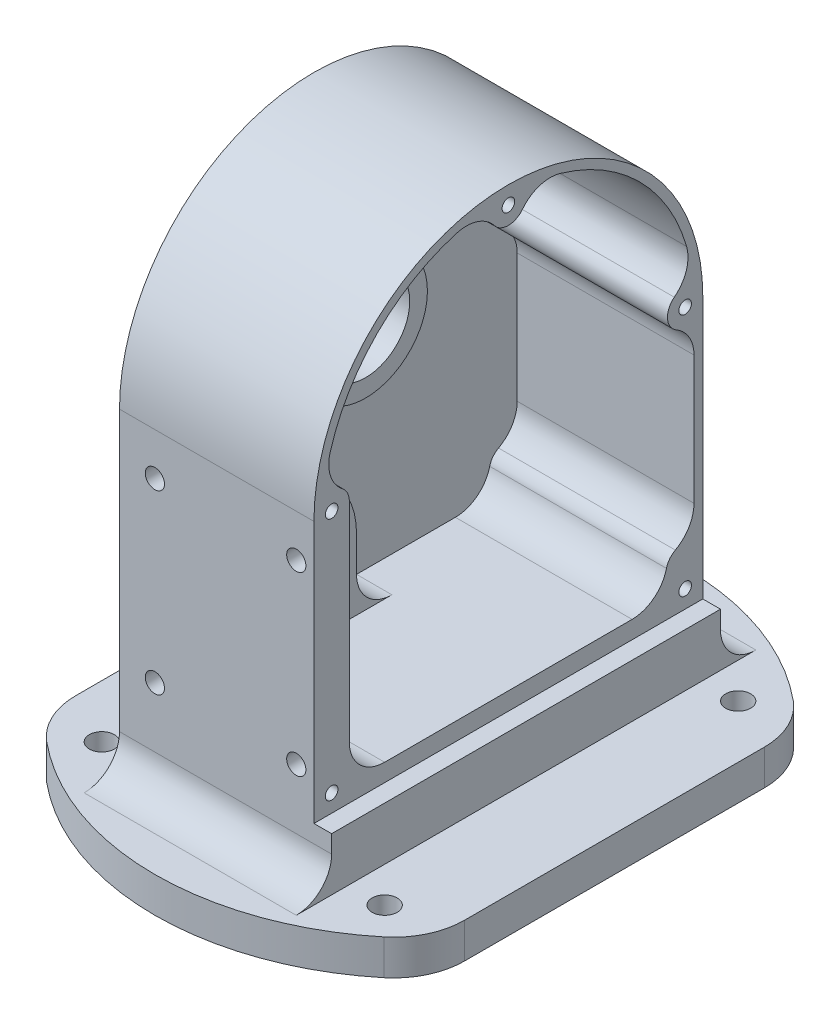
SolidWorks part; units mm, degrees
material "6061 Alloy"
ref_plane "Front Plane" through (0, 0, 0) normal (0, 0, 1) x (1, 0, 0)
ref_plane "Top Plane" through (0, 0, 0) normal (0, 1, 0) x (1, 0, 0)
ref_plane "Right Plane" through (0, 0, 0) normal (1, 0, 0) x (0, 0, -1)
sketch "Sketch1" plane through (0, 0, 0) normal (1, 0, 0) x (0, 0, -1)
  line L2 (-34.925, 5.715) -> (-34.925, -41.275)
  line L3 (-34.925, -41.275) -> (34.925, -41.275)
  line L4 (34.925, 5.715) -> (34.925, -41.275)
  arc A0 (34.925, 5.715) -> (-34.925, 5.715) centre (0, 5.715) ccw
  point P0 (0, 0)
  dimension "D1" = 41.275
  dimension "D3" = 46.99
  dimension "D4" = 69.85
extrude "Boss-Extrude1" add sketch "Sketch1" along normal mid plane 34.925
sketch "Sketch2" plane through (-17.4625, 0, 0) normal (-1, 0, 0) x (0, 0, 1)
  line L2 (34.925, 5.715) -> (34.925, -41.275) construction
  circle A0 centre (15.875, -25.3935) radius 11.254
  point P2 (0, 5.715)
  dimension "D1" = 22.508
  dimension "D2" = 34.925
  dimension "D3" = 19.05
extrude "Cut-Extrude1" cut sketch "Sketch2" against normal blind 6.35
sketch "Sketch3" plane through (-11.1125, 0, 0) normal (-1, 0, 0) x (0, 0, 1)
  circle A0 centre (15.875, -25.3935) radius 5.127
  dimension "D1" = 10.254
extrude "Cut-Extrude2" cut sketch "Sketch3" against normal through all
sketch "Sketch4" plane through (17.4625, 0, 0) normal (1, 0, 0) x (0, 0, -1)
  circle A0 centre (-15.875, -25.3935) radius 11.254
  circle A1 centre (-15.875, -25.3935) radius 11.254 construction
extrude "Cut-Extrude3" cut sketch "Sketch4" against normal offset from surface (25.4 mm away) 3.175 up to face at (-11.1125, -25.3935, 21.002)
hole_wizard "CSK for M2.5 Flat Head Machine Screw1" positions "Sketch6" profile "Sketch5" countersink size "M2.5" standard "Ansi Metric" end condition through all
sketch "Sketch6" plane through (-7.9375, 0, 0) normal (1, 0, 0) x (0, 0, -1)
  line L0 (-15.875, -18.3935) -> (-15.875, -25.3935) construction
  circle A0 centre (-15.875, -25.3935) radius 5.127 construction
  point P0 (-15.875, -18.3935)
  dimension "D1" = 7
sketch "Sketch5" plane through (-7.9375, -18.3935, 15.875) normal (0, 1, 0) x (0, 0, -1)
  line L0 (0, 0) -> (0, 9.525)
  line L1 (0, 9.525) -> (1.45, 9.525)
  line L2 (1.45, 9.525) -> (1.45, 1.3)
  line L3 (1.45, 1.3) -> (2.75, 0)
  line L5 (2.75, 0) -> (0, 0)
  line L6 (-1.45, 1.3) -> (-2.75, 0) construction
  line L11 (0, -6.35) -> (0, 107.95) construction
  dimension "Thru Hole Dia." = 2.9
  dimension "Thru Hole Depth" = 9.525
  dimension "Near C'Sink Dia." = 5.5
  dimension "Near C'Sink Angle" = 90
pattern_circular "CirPattern1" count 3 over 360 about axis through (0, -25.3935, 15.875) along (1, 0, 0) of "CSK for M2.5 Flat Head Machine Screw1"
sketch "Sketch7" plane through (17.4625, 0, 0) normal (1, 0, 0) x (0, 0, -1)
  line L0 (28.575, -38.1) -> (-28.575, -38.1)
  line L1 (-28.575, -38.1) -> (-28.575, 5.715)
  line L3 (28.575, 5.715) -> (28.575, -38.1)
  line L5 (34.925, -41.275) -> (34.925, 5.715) construction
  line L6 (-34.925, 5.715) -> (-34.925, -41.275) construction
  line L7 (-34.925, -41.275) -> (34.925, -41.275) construction
  arc A0 (28.575, 5.715) -> (-28.575, 5.715) centre (0, 5.715) ccw
  dimension "D2" = 6.35
  dimension "D3" = 6.35
  dimension "D4" = 3.175
extrude "Cut-Extrude4" cut sketch "Sketch7" against normal up to surface (25.4 mm away) up to face at (-7.9375, -25.3935, 27.129)
sketch "Sketch8" plane through (-7.9375, 0, 0) normal (1, 0, 0) x (0, 0, -1)
  line L0 (-28.575, 5.715) -> (-28.575, -38.1) construction
  line L2 (-15.875, -11.3935) -> (-28.575, -11.3935)
  line L3 (-28.575, -38.1) -> (28.575, -38.1) construction
  line L4 (-1.875, -38.1) -> (-1.875, -25.3935)
  line L6 (-28.575, -11.3935) -> (-28.575, 5.715)
  line L8 (28.575, 5.715) -> (28.575, -38.1)
  line L9 (28.575, -38.1) -> (-1.875, -38.1)
  arc A0 (-1.875, -25.3935) -> (-15.875, -11.3935) centre (-15.875, -25.3935) ccw
  arc A1 (28.575, 5.715) -> (-28.575, 5.715) centre (0, 5.715) ccw construction
  arc A2 (28.575, 5.715) -> (-28.575, 5.715) centre (0, 5.715) ccw construction
  arc A3 (28.575, 5.715) -> (-28.575, 5.715) centre (0, 5.715) ccw
  dimension "D1" = 14
extrude "Cut-Extrude5" cut sketch "Sketch8" against normal offset from surface (6.35 mm away) 3.175 up to face at (-17.4625, -25.3935, 27.129)
fillet "Fillet1" radius 6.35 4 edges at (4.7625, -38.1, 28.575) (1.5875, -38.1, -28.575) (-11.1125, -38.1, 1.875) (-11.1125, -11.3935, 28.575)
sketch "Sketch9" plane through (-14.2875, 0, 0) normal (1, 0, 0) x (0, 0, -1)
  circle A0 centre (0, 5.715) radius 7.9375
  arc A1 (34.925, 5.715) -> (-34.925, 5.715) centre (0, 5.715) ccw construction
  dimension "D2" = 15.875
extrude "Cut-Extrude6" cut sketch "Sketch9" against normal through all
chamfer "Chamfer1" distance 1.27 angle 45 1 edges at (-17.4625, -25.3935, 27.129)
sketch "Sketch10" plane through (-14.2875, 0, 0) normal (1, 0, 0) x (0, 0, -1)
  circle A0 centre (0, 5.715) radius 11.1125
  circle A1 centre (0, 5.715) radius 7.9375 construction
  circle A2 centre (0, 5.715) radius 7.9375
  dimension "D1" = 3.175
extrude "Boss-Extrude2" add sketch "Sketch10" along normal offset from surface (6.096 mm away) 9.271 up to face at (-17.4625, -25.3935, 3.351)
hole_wizard "#4-40 Tapped Hole2" positions "Sketch16" profile "Sketch15" tap size "#4-40" standard "Ansi Inch"
sketch "Sketch16" plane through (17.4625, 0, 0) normal (1, 0, 0) x (0, 0, -1)
  line L1 (-31.75, 5.715) -> (31.75, 5.715) construction
  line L2 (-31.75, 5.715) -> (-31.75, -38.1) construction
  line L3 (-31.75, -38.1) -> (31.75, -38.1) construction
  line L4 (31.75, 5.715) -> (31.75, -38.1) construction
  line L5 (-34.925, -41.275) -> (34.925, -41.275) construction
  circle A1 centre (0, 5.715) radius 31.75
  arc A2 (28.575, 5.715) -> (-28.575, 5.715) centre (0, 5.715) ccw construction
  point P0 (0, 37.465)
  point P1 (-31.75, 5.715)
  point P3 (31.75, 5.715)
  point P5 (31.75, -38.1)
  point P7 (-31.75, -38.1)
  dimension "D1" = 3.175
  dimension "D2" = 3.175
sketch "Sketch15" plane through (17.4625, 37.465, 0) normal (0, 1, 0) x (0, 0, -1)
  line L0 (0, 0) -> (0, 13.3792)
  line L1 (0, 13.3792) -> (1.1303, 12.7)
  line L2 (1.1303, 12.7) -> (1.1303, 0)
  line L5 (1.1303, 0) -> (0, 0)
  line L10 (0, 13.3792) -> (-1.1303, 12.7) construction
  line L11 (0, -6.35) -> (0, 107.95) construction
  dimension "Tap Drill Dia." = 2.2606
  dimension "Tap Drill Depth" = 12.7
  dimension "Drill Angle" = 118
cosmetic thread "Hole Thread5" parameters "D1"=5.588, "D2"=2.8448
cosmetic thread "Hole Thread6" parameters "D1"=5.588, "D2"=2.8448
cosmetic thread "Hole Thread7" parameters "D1"=5.588, "D2"=2.8448
cosmetic thread "Hole Thread8" parameters "D1"=5.588, "D2"=2.8448
cosmetic thread "Hole Thread9" parameters "D1"=5.588, "D2"=2.8448
sketch "Sketch17" plane through (17.4625, 0, 0) normal (1, 0, 0) x (0, 0, -1)
  line L0 (-33.3375, -2.5339) -> (-33.3375, -25.6016)
  line L1 (33.3375, -2.5339) -> (33.3375, -25.6016)
  line L3 (-28.575, 5.715) -> (-28.575, -31.75)
  line L5 (28.575, 5.715) -> (28.575, -31.75)
  line L6 (34.925, -41.275) -> (34.925, 5.715) construction
  line L7 (-34.925, 5.715) -> (-34.925, -41.275) construction
  arc A0 (-30.1625, 2.9654) -> (-29.8053, 8.2247) centre (-31.75, 5.715) ccw
  arc A1 (-2.5097, 35.5203) -> (2.5097, 35.5203) centre (0, 37.465) ccw
  arc A2 (29.8053, 8.2247) -> (30.1625, 2.9654) centre (31.75, 5.715) ccw
  arc A3 (34.925, 5.715) -> (-34.925, 5.715) centre (0, 5.715) ccw construction
  arc A4 (32.0138, 15.0158) -> (9.3008, 37.7288) centre (0, 5.715) ccw
  arc A5 (28.575, 5.715) -> (-28.575, 5.715) centre (0, 5.715) ccw
  arc A6 (28.575, 5.715) -> (-28.575, 5.715) centre (0, 5.715) ccw construction
  arc A7 (-29.8053, 8.2247) -> (-32.0138, 15.0158) centre (-25.9159, 13.2442) cw
  arc A8 (32.0138, 15.0158) -> (29.8053, 8.2247) centre (25.9159, 13.2442) cw
  arc A9 (-2.5097, 35.5203) -> (-9.3008, 37.7288) centre (-7.5292, 31.6309) ccw
  arc A10 (2.5097, 35.5203) -> (9.3008, 37.7288) centre (7.5292, 31.6309) cw
  arc A11 (-9.3008, 37.7288) -> (-32.0138, 15.0158) centre (0, 5.715) ccw
  arc A12 (28.575, -31.75) -> (33.3375, -25.6016) centre (26.9875, -25.6016) ccw
  arc A13 (30.1625, 2.9654) -> (33.3375, -2.5339) centre (26.9875, -2.5339) cw
  arc A14 (-30.1625, 2.9654) -> (-33.3375, -2.5339) centre (-26.9875, -2.5339) ccw
  arc A15 (-28.575, -31.75) -> (-33.3375, -25.6016) centre (-26.9875, -25.6016) cw
  arc M6 (-28.575, 5.715) -> (28.575, 5.715) centre (0, 5.715) cw
  line M7 (28.575, 5.715) -> (28.575, -31.75)
  line M11 (-28.575, -31.75) -> (-28.575, 5.715)
  dimension "D1" = 1.5875
  dimension "D2" = 6.35
  dimension "D3" = 6.35
  dimension "D4" = 1.5875
  dimension "D5" = 1.5875
extrude "Cut-Extrude7" cut sketch "Sketch17" against normal up to surface (25.4 mm away) contours A9 A11 A7 A0 A1 M6 | A10 A1 A2 A8 A4 M6 | A13 A2 A12 L1 M7 | A15 A0 A14 L0 M11 up to face at (-7.9375, -25.3935, 15.875)
fillet "Fillet3" radius 3.175 2 edges at (4.7625, -31.75, -28.575) (4.7625, -31.75, 28.575)
sketch "Sketch31" plane through (-7.9375, 0, 0) normal (1, 0, 0) x (0, 0, -1)
  line L0 (-33.3375, -2.5339) -> (-33.3375, -25.6016) construction
  line L1 (33.3375, -2.5339) -> (33.3375, -25.6016) construction
  line L2 (-33.3375, -2.5339) -> (-33.3375, -11.3935)
  line L3 (33.3375, -2.5339) -> (33.3375, -25.6016)
  line L4 (-22.225, -11.3935) -> (-33.3375, -11.3935)
  line L5 (-28.575, -5.0435) -> (-28.575, 5.715) construction
  line L6 (28.575, 5.715) -> (28.575, -31.75) construction
  line L7 (-28.575, -5.0435) -> (-28.575, 5.715)
  line L8 (28.575, 5.715) -> (28.575, -31.75)
  arc A0 (-30.1625, 2.9654) -> (-33.3375, -2.5339) centre (-26.9875, -2.5339) ccw construction
  arc A1 (-30.1625, 2.9654) -> (-29.8053, 8.2247) centre (-31.75, 5.715) ccw construction
  arc A2 (-32.0138, 15.0158) -> (-29.8053, 8.2247) centre (-25.9159, 13.2442) ccw construction
  arc A3 (-9.3008, 37.7288) -> (-32.0138, 15.0158) centre (0, 5.715) ccw construction
  arc A4 (-2.5097, 35.5203) -> (-9.3008, 37.7288) centre (-7.5292, 31.6309) ccw construction
  arc A5 (-2.5097, 35.5203) -> (2.5097, 35.5203) centre (0, 37.465) ccw construction
  arc A6 (9.3008, 37.7288) -> (2.5097, 35.5203) centre (7.5292, 31.6309) ccw construction
  arc A7 (32.0138, 15.0158) -> (9.3008, 37.7288) centre (0, 5.715) ccw construction
  arc A8 (29.8053, 8.2247) -> (32.0138, 15.0158) centre (25.9159, 13.2442) ccw construction
  arc A9 (29.8053, 8.2247) -> (30.1625, 2.9654) centre (31.75, 5.715) ccw construction
  arc A10 (33.3375, -2.5339) -> (30.1625, 2.9654) centre (26.9875, -2.5339) ccw construction
  arc A11 (29.9827, -31.2009) -> (33.3375, -25.6016) centre (26.9875, -25.6016) ccw construction
  arc A12 (29.9827, -31.2009) -> (28.3952, -33.2503) centre (31.4803, -34.0005) ccw construction
  arc A13 (-30.1625, 2.9654) -> (-33.3375, -2.5339) centre (-26.9875, -2.5339) ccw
  arc A14 (-30.1625, 2.9654) -> (-29.8053, 8.2247) centre (-31.75, 5.715) ccw
  arc A15 (-32.0138, 15.0158) -> (-29.8053, 8.2247) centre (-25.9159, 13.2442) ccw
  arc A16 (-9.3008, 37.7288) -> (-32.0138, 15.0158) centre (0, 5.715) ccw
  arc A17 (-2.5097, 35.5203) -> (-9.3008, 37.7288) centre (-7.5292, 31.6309) ccw
  arc A18 (-2.5097, 35.5203) -> (2.5097, 35.5203) centre (0, 37.465) ccw
  arc A19 (9.3008, 37.7288) -> (2.5097, 35.5203) centre (7.5292, 31.6309) ccw
  arc A20 (32.0138, 15.0158) -> (9.3008, 37.7288) centre (0, 5.715) ccw
  arc A21 (29.8053, 8.2247) -> (32.0138, 15.0158) centre (25.9159, 13.2442) ccw
  arc A22 (29.8053, 8.2247) -> (30.1625, 2.9654) centre (31.75, 5.715) ccw
  arc A23 (33.3375, -2.5339) -> (30.1625, 2.9654) centre (26.9875, -2.5339) ccw
  arc A24 (29.9827, -31.2009) -> (33.3375, -25.6016) centre (26.9875, -25.6016) ccw
  arc A25 (29.9827, -31.2009) -> (28.3952, -33.2503) centre (31.4803, -34.0005) ccw
  arc A26 (-28.575, -5.0435) -> (-22.225, -11.3935) centre (-22.225, -5.0435) ccw construction
  arc A27 (28.575, 5.715) -> (-28.575, 5.715) centre (0, 5.715) ccw construction
  arc A28 (22.225, -38.1) -> (28.575, -31.75) centre (22.225, -31.75) ccw construction
  arc A29 (-28.575, -5.0435) -> (-22.225, -11.3935) centre (-22.225, -5.0435) ccw
  arc A30 (28.575, 5.715) -> (-28.575, 5.715) centre (0, 5.715) ccw
  arc A31 (28.3952, -33.2503) -> (28.575, -31.75) centre (22.225, -31.75) ccw
  arc M7 (-22.225, -11.3935) -> (-28.575, -5.0435) centre (-22.225, -5.0435) cw
  line M8 (-28.575, -5.0435) -> (-28.575, 5.715)
  arc M9 (-28.575, 5.715) -> (-30.1625, 2.9654) centre (-31.75, 5.715) cw
  arc M10 (-30.1625, 2.9654) -> (-33.3375, -2.5339) centre (-26.9875, -2.5339) ccw
  line M11 (-33.3375, -2.5339) -> (-33.3375, -25.6016)
extrude "Cut-Extrude13" cut sketch "Sketch31" against normal up to surface (6.35 mm away) contours L4 M7 M8 M9 M10 M11 | A30 A18 A17 A16 A15 A14 | A30 A22 A21 A20 A19 A18 | A31 A25 A24 L3 A23 A22 L8 up to face at (-14.2875, -15.3965, 1.3566)
sketch "Sketch21" plane through (0, -41.275, 0) normal (0, -1, 0) x (1, 0, 0)
  line L1 (-33.3375, -32.3788) -> (-33.3375, 32.3788)
  line L2 (-33.3375, 0) -> (36.5125, 0) construction
  line L3 (36.5125, -32.3788) -> (36.5125, 32.3788)
  line L4 (0, 34.925) -> (0, -34.925) construction
  line L6 (17.4625, 34.925) -> (-17.4625, 34.925) construction
  line L7 (17.4625, -34.925) -> (-17.4625, -34.925) construction
  arc A0 (-33.3375, -32.3788) -> (36.5125, -32.3788) centre (1.5875, 0) ccw
  arc A1 (36.5125, 32.3788) -> (-33.3375, 32.3788) centre (1.5875, 0) ccw
  dimension "D1" = 95.25
  dimension "D2" = 69.85
  dimension "D3" = 33.3375
extrude "Boss-Extrude3" add sketch "Sketch21" along normal blind 15.875
sketch "Sketch22" plane through (0, 0, 34.925) normal (0, 0, 1) x (1, 0, 0)
  line L0 (20.6375, -41.275) -> (20.6375, -50.8)
  line L2 (20.6375, -50.8) -> (36.5125, -50.8)
  line L3 (36.5125, -50.8) -> (36.5125, -41.275)
  line L4 (36.5125, -41.275) -> (20.6375, -41.275)
  line L5 (-33.3375, -57.15) -> (36.5125, -57.15) construction
  line L6 (36.5125, -41.275) -> (-33.3375, -41.275) construction
  line L7 (36.5125, -57.15) -> (36.5125, -41.275) construction
  dimension "D1" = 3.175
  dimension "D2" = 6.35
extrude "Cut-Extrude8" cut sketch "Sketch22" against normal through all and the other way up to next
mirror "Mirror1" about plane through (0, 0, 0) normal (1, 0, 0) of "Cut-Extrude8"
hole_wizard "#8 Clearance Hole1" positions "Sketch24" profile "Sketch23" hole size "#8" standard "Ansi Inch"
sketch "Sketch24" plane through (0, -57.15, 0) normal (0, -1, 0) x (1, 0, 0)
  line L1 (-23.8125, 31.75) -> (26.9875, 31.75) construction
  line L2 (-23.8125, 31.75) -> (-23.8125, -31.75) construction
  line L3 (-23.8125, -31.75) -> (26.9875, -31.75) construction
  line L4 (26.9875, 31.75) -> (26.9875, -31.75) construction
  line L7 (1.5875, 31.75) -> (1.5875, -31.75) construction
  point P0 (26.9875, 31.75)
  point P70 (-23.8125, 31.75)
  point P72 (-23.8125, -31.75)
  point P74 (26.9875, -31.75)
  point P90 (1.5875, 0)
  dimension "D1" = 63.5
  dimension "D2" = 50.8
  dimension "D3" = 1.5875
sketch "Sketch23" plane through (26.9875, -57.15, 31.75) normal (1, 0, 0) x (0, 0, -1)
  line L0 (0, 0) -> (0, 7.7007)
  line L1 (0, 7.7007) -> (2.2479, 6.35)
  line L2 (2.2479, 6.35) -> (2.2479, 0)
  line L5 (2.2479, 0) -> (0, 0)
  line L10 (0, 7.7007) -> (-2.2479, 6.35) construction
  line L11 (0, -6.35) -> (0, 107.95) construction
  dimension "Hole Dia." = 4.4958
  dimension "Hole Depth" = 6.35
  dimension "Drill Angle" = 118
sketch "Sketch25" plane through (0, -57.15, 0) normal (0, -1, 0) x (1, 0, 0)
  line L1 (-14.2875, 31.75) -> (14.2875, 31.75)
  line L2 (-14.2875, 31.75) -> (-14.2875, -31.75)
  line L3 (-14.2875, -31.75) -> (14.2875, -31.75)
  line L4 (14.2875, 31.75) -> (14.2875, -31.75)
  line L5 (-14.2875, 31.75) -> (14.2875, -31.75) construction
  line L6 (-14.2875, -31.75) -> (14.2875, 31.75) construction
  circle A0 centre (-23.8125, 31.75) radius 2.2479 construction
  point P0 (0, 0)
  dimension "D1" = 63.5
  dimension "D2" = 9.525
extrude "Cut-Extrude9" cut sketch "Sketch25" against normal blind 3.175
sketch "Sketch26" plane through (0, -53.975, 0) normal (0, -1, 0) x (1, 0, 0)
  line L0 (14.2875, 31.75) -> (-14.2875, 31.75) construction
  line L1 (-12.7, 28.575) -> (12.7, 28.575)
  line L2 (-12.7, 28.575) -> (-12.7, -28.575)
  line L3 (-12.7, -28.575) -> (12.7, -28.575)
  line L4 (12.7, 28.575) -> (12.7, -28.575)
  line L5 (-12.7, 28.575) -> (12.7, -28.575) construction
  line L6 (-12.7, -28.575) -> (12.7, 28.575) construction
  point P0 (0, 0)
  point P6 (0, 31.75)
  dimension "D1" = 25.4
  dimension "D2" = 3.175
extrude "Cut-Extrude10" cut sketch "Sketch26" against normal offset from surface (12.7 mm away) 3.175 up to face at (-1.5875, -38.1, -1.4917)
fillet "Fillet5" radius 3.175 12 edges at (14.2875, -55.5625, 31.75) (-14.2875, -55.5625, 31.75) (-14.2875, -55.5625, -31.75) (14.2875, -55.5625, -31.75) (12.7, -47.625, 28.575) (-12.7, -47.625, 28.575) (-12.7, -47.625, -28.575) (12.7, -47.625, -28.575) (0, -41.275, -28.575) (0, -41.275, 28.575) (12.7, -41.275, 0) (-12.7, -41.275, 0)
sketch "Sketch28" plane through (0, 0, 34.925) normal (0, 0, 1) x (1, 0, 0)
  line L0 (-17.4625, -41.275) -> (-17.4625, -50.8)
  line L1 (-17.4625, -41.275) -> (-20.6375, -41.275)
  line L2 (-33.3375, -50.8) -> (-17.4625, -50.8)
  line L3 (-20.6375, -41.275) -> (-33.3375, -50.8)
extrude "Cut-Extrude11" cut sketch "Sketch28" against normal through all and the other way up to next
fillet "Fillet7" radius 12.7 4 edges at (36.5125, -53.975, -32.3788) (36.5125, -53.975, 32.3788) (-33.3375, -53.975, 32.3788) (-33.3375, -53.975, -32.3788)
fillet "Fillet8" radius 3.175 1 edges at (-14.2875, 5.715, -11.1125)
sketch "Sketch30" plane through (0, -41.275, 0) normal (0, 1, 0) x (1, 0, 0)
  line L0 (17.4625, 34.925) -> (-17.4625, 34.925) construction
  line L2 (20.6375, 34.925) -> (-17.4625, 34.925)
  line L3 (-17.4625, 43.649) -> (-17.4625, 34.925)
  line L5 (17.4625, -34.925) -> (-17.4625, -34.925) construction
  line L7 (20.6375, -43.649) -> (20.6375, -34.925)
  line L8 (20.6375, -34.925) -> (-17.4625, -34.925)
  line L9 (-17.4625, -34.925) -> (-17.4625, -43.649)
  line L11 (20.6375, 34.925) -> (20.6375, 43.649)
  line L12 (20.6375, -43.649) -> (20.6375, 43.649) construction
  line L13 (20.6375, -43.649) -> (20.6375, 43.649) construction
  arc A0 (20.6375, 43.649) -> (-17.4625, 43.649) centre (1.5875, 0) ccw construction
  arc A1 (20.6375, 43.649) -> (-17.4625, 43.649) centre (1.5875, 0) ccw
  arc A2 (-17.4625, -43.649) -> (20.6375, -43.649) centre (1.5875, 0) ccw construction
  arc A3 (-17.4625, -43.649) -> (20.6375, -43.649) centre (1.5875, 0) ccw
extrude "Cut-Extrude12" cut sketch "Sketch30" against normal up to surface (9.525 mm away)
sketch "Sketch33" plane through (17.4625, 0, 0) normal (1, 0, 0) x (0, 0, -1)
  line L0 (-28.5823, 5.4999) -> (-28.5823, -32.7035)
  line L1 (-33.3375, -2.5339) -> (-33.3375, -25.6016) construction
  line L2 (-33.3375, -2.5339) -> (-33.3375, -25.6016)
  arc A0 (-30.1625, 2.9654) -> (-29.8053, 8.2247) centre (-31.75, 5.715) ccw construction
  arc A1 (-28.3952, -33.2503) -> (-29.9827, -31.2009) centre (-31.4803, -34.0005) ccw construction
  arc A2 (-33.3375, -25.6016) -> (-29.9827, -31.2009) centre (-26.9875, -25.6016) ccw construction
  arc A3 (-30.1625, 2.9654) -> (-33.3375, -2.5339) centre (-26.9875, -2.5339) ccw construction
  arc A4 (-28.5823, -32.7035) -> (-29.9827, -31.2009) centre (-31.4803, -34.0005) ccw
  arc A5 (-33.3375, -25.6016) -> (-29.9827, -31.2009) centre (-26.9875, -25.6016) ccw
  arc A6 (-30.1625, 2.9654) -> (-33.3375, -2.5339) centre (-26.9875, -2.5339) ccw
  arc A7 (-30.1625, 2.9654) -> (-28.5823, 5.4999) centre (-31.75, 5.715) ccw
extrude "Boss-Extrude4" add sketch "Sketch33" against normal up to surface (31.75 mm away) up to face at (-14.2875, 5.715, -14.2875)
fillet "Fillet11" radius 6.35 1 edges at (4.7625, -32.7035, 28.5823)
sketch "Sketch32" plane through (0, 0, 34.925) normal (0, 0, 1) x (1, 0, 0)
  line L0 (20.6375, -46.0375) -> (-17.4625, -46.0375) construction
  line L1 (20.6375, -50.8) -> (20.6375, -41.275) construction
  line L2 (-17.4625, 5.715) -> (-17.4625, -50.8) construction
  line L3 (1.5875, -46.0375) -> (1.5875, 40.64) construction
  line L4 (17.4625, 40.64) -> (-17.4625, 40.64) construction
  line L5 (20.6375, -50.8) -> (-17.4625, -50.8) construction
  line L6 (-11.1125, -33.655) -> (14.2875, -33.655) construction
  line L7 (-11.1125, -33.655) -> (-11.1125, -1.905) construction
  line L8 (-11.1125, -1.905) -> (14.2875, -1.905) construction
  line L9 (14.2875, -33.655) -> (14.2875, -1.905) construction
  line L10 (-11.1125, -33.655) -> (14.2875, -1.905) construction
  line L11 (-11.1125, -1.905) -> (14.2875, -33.655) construction
  point P10 (1.5875, -17.78)
  dimension "D1" = 31.75
  dimension "D2" = 25.4
  dimension "D3" = 33.02
hole_wizard "#8-32 Tapped Hole2" positions "Sketch35" profile "Sketch36" tap size "#8-32" standard "Ansi Inch"
sketch "Sketch35" plane through (0, 0, 34.925) normal (0, 0, 1) x (1, 0, 0)
  point P0 (-11.1125, -1.905)
  point P1 (14.2875, -1.905)
  point P4 (-11.1125, -33.655)
  point P7 (14.2875, -33.655)
cosmetic thread "Hole Thread11" parameters "D1"=7.4914, "D2"=4.1656
cosmetic thread "Hole Thread12" parameters "D1"=7.62, "D2"=4.1656
cosmetic thread "Hole Thread13" parameters "D1"=6.3427, "D2"=4.1656
cosmetic thread "Hole Thread14" parameters "D1"=6.3427, "D2"=4.1656
sketch "Sketch36" plane through (-11.1125, -1.905, 34.925) normal (1, 0, 0) x (0, -1, 0)
  line L0 (0, 0) -> (0, 8.6578)
  line L1 (0, 8.6578) -> (1.7272, 7.62)
  line L2 (1.7272, 7.62) -> (1.7272, 0)
  line L5 (1.7272, 0) -> (0, 0)
  line L10 (0, 8.6578) -> (-1.7272, 7.62) construction
  line L11 (0, -6.35) -> (0, 107.95) construction
  dimension "Tap Drill Dia." = 3.4544
  dimension "Tap Drill Depth" = 7.62
  dimension "Drill Angle" = 118
fillet "Fillet12" radius 6.35 1 edges at (-11.1125, -11.3935, 28.5823)
fillet "Fillet13" radius 6.35 2 edges at (1.5875, -50.8, -34.925) (1.5875, -50.8, 34.925)
